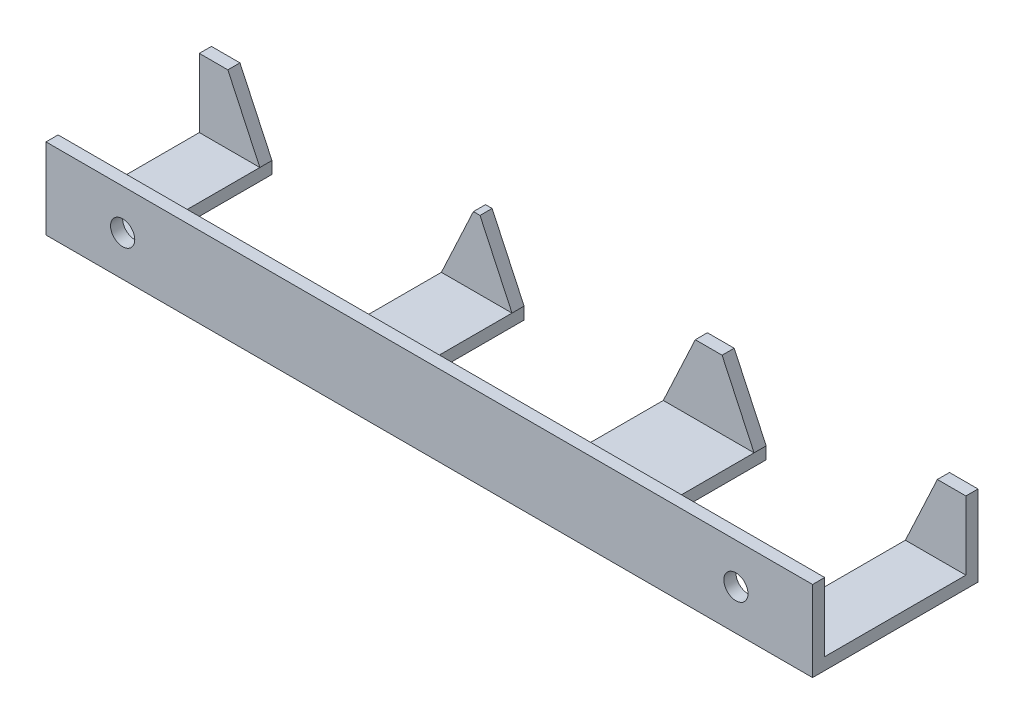
SolidWorks part; units mm, degrees
ref_plane "Přední rovina" through (0, 0, 0) normal (0, 0, 1) x (1, 0, 0)
ref_plane "Horní rovina" through (0, 0, 0) normal (0, 1, 0) x (1, 0, 0)
ref_plane "Pravá rovina" through (0, 0, 0) normal (1, 0, 0) x (0, 0, -1)
sketch "Skica1" plane through (0, 0, 0) normal (0, 0, 1) x (1, 0, 0)
  line L1 (-95, 10) -> (95, 10)
  line L2 (-95, 10) -> (-95, -10)
  line L3 (-95, -10) -> (95, -10)
  line L4 (95, 10) -> (95, -10)
  line L5 (-95, 10) -> (95, -10) construction
  line L6 (-95, -10) -> (95, 10) construction
  point P0 (0, 0)
  dimension "D1" = 20
  dimension "D2" = 190
extrude "Přidat vysunutím1" add sketch "Skica1" along normal blind 41
sketch "Skica2" plane through (0, 10, 0) normal (0, 1, 0) x (1, 0, 0)
  line L0 (0, 0) -> (0, -41)
  line L1 (95, 0) -> (-95, 0) construction
  line L2 (95, -41) -> (-95, -41) construction
  line L3 (95, -41) -> (95, 0) construction
  line L4 (-95, -3) -> (95, -3)
  line L5 (-95, -3) -> (-95, -38)
  line L6 (-95, -38) -> (95, -38)
  line L7 (95, -3) -> (95, -38)
  line L8 (-95, -3) -> (95, -38) construction
  line L9 (-95, -38) -> (95, -3) construction
  point P6 (0, -20.5)
  line M3 (-95, 0) -> (-95, -41)
  line M5 (95, -41) -> (95, 0)
  dimension "D1" = 35
extrude "Odebrat vysunutím1" cut sketch "Skica2" against normal blind 17 contours L6 L0 L4 M3 | L0 L6 L4 M5
sketch "Skica3" plane through (0, 0, 0) normal (0, 0, -1) x (-1, 0, 0)
  line L0 (95, -10) -> (-95, -10) construction
  line L1 (-80, -10) -> (-42.5, -10)
  line L2 (-80, -10) -> (-80, 10)
  line L3 (-80, 10) -> (-42.5, 10)
  line L4 (-42.5, -10) -> (-42.5, 10)
  line L5 (-95, 10) -> (95, 10) construction
  line L7 (-20, -10) -> (17.5, -10)
  line L8 (-20, -10) -> (-20, 10)
  line L9 (-20, 10) -> (17.5, 10)
  line L10 (17.5, -10) -> (17.5, 10)
  line L11 (35, -10) -> (80, -10)
  line L12 (35, -10) -> (35, 10)
  line L13 (35, 10) -> (80, 10)
  line L14 (80, -10) -> (80, 10)
  dimension "D1" = 15
  dimension "D2" = 37.5
  dimension "D3" = 22.5
  dimension "D4" = 37.5
  dimension "D5" = 17.5
  dimension "D6" = 45
extrude "Odebrat vysunutím2" cut sketch "Skica3" against normal blind 38
sketch "Skica4" plane through (0, 0, 41) normal (0, 0, 1) x (1, 0, 0)
  line L0 (0, 10) -> (0, -10)
  line L1 (95, 10) -> (-95, 10) construction
  line L2 (-95, -10) -> (95, -10) construction
  line L3 (0, 0) -> (-90.8204, 0)
  line L4 (0, 0) -> (91.5128, 0)
  point P8 (76, 0)
  point P9 (-76, 0)
  dimension "D1" = 76
  dimension "D2" = 76
hole_wizard "Díry pro kolík, velikost mm1" positions "Skica5" profile "Skica6" hole size "Ø6.0" standard "ANSI Metric" end condition through all
sketch "Skica5" plane through (0, 0, 41) normal (0, 0, 1) x (1, 0, 0)
  point P0 (-76, 0)
  point P3 (76, 0)
sketch "Skica6" plane through (-76, 0, 41) normal (1, 0, 0) x (0, -1, 0)
  line L0 (0, 0) -> (0, 41)
  line L1 (0, 41) -> (3, 41)
  line L2 (3, 41) -> (3, 0)
  line L5 (3, 0) -> (0, 0)
  line L11 (0, -6.35) -> (0, 107.95) construction
  dimension "Průměr díry skrz" = 6
  dimension "Hloubka díry skrz" = 41
chamfer "Zkosení2" distance 17 angle 25 3 edges at (-35, 10, 1.5) (20, 10, 1.5) (80, 10, 1.5)
chamfer "Zkosení3" distance 17 angle 25 3 edges at (-80, 10, 1.5) (-17.5, 10, 1.5) (42.5, 10, 1.5)
